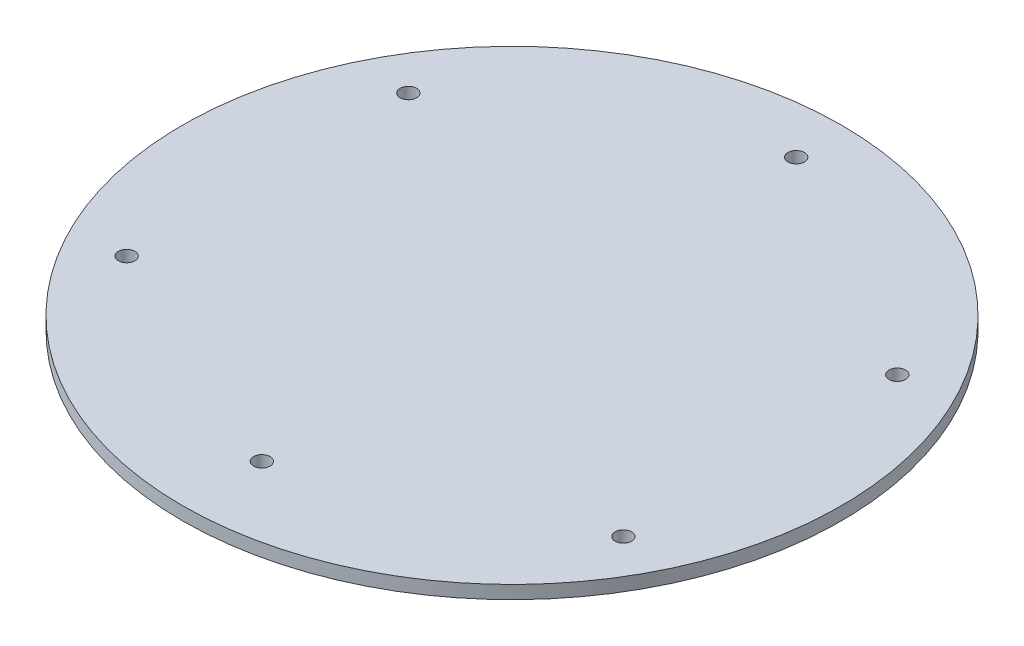
SolidWorks part; units mm, degrees
ref_plane "Front Plane" through (0, 0, 0) normal (0, 0, 1) x (1, 0, 0)
ref_plane "Top Plane" through (0, 0, 0) normal (0, 1, 0) x (1, 0, 0)
ref_plane "Right Plane" through (0, 0, 0) normal (1, 0, 0) x (0, 0, -1)
sketch "Sketch1" plane through (0, 0, 0) normal (0, 1, 0) x (1, 0, 0)
  circle A0 centre (1.9537, -0.6413) radius 50
  circle A1 centre (-35.1242, 20.707) radius 1.25
  circle A2 centre (2.7295, 41.6945) radius 1.25
  circle A3 centre (38.9808, 20.795) radius 1.25
  circle A4 centre (39.4592, -21.2469) radius 1.25
  circle A5 centre (2.1533, -38.7932) radius 1.25
  circle A6 centre (-35.0733, -22.0776) radius 1.25
  point P0 (0, 0)
extrude "Boss-Extrude5" add sketch "Sketch1" along normal blind 2
